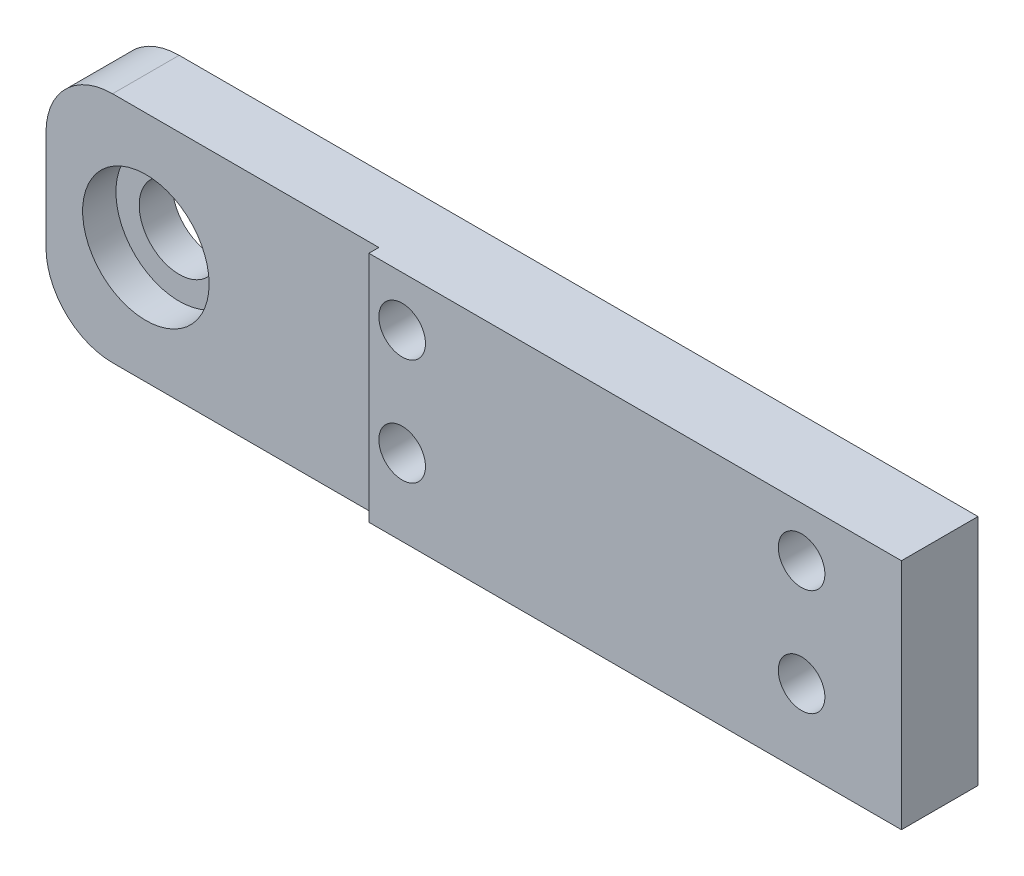
SolidWorks part; units mm, degrees
material "SKD11淬火HRC56-60"
ref_plane "前基準面" through (0, 0, 0) normal (0, 0, 1) x (1, 0, 0)
ref_plane "上基準面" through (0, 0, 0) normal (0, 1, 0) x (1, 0, 0)
ref_plane "右基準面" through (0, 0, 0) normal (1, 0, 0) x (0, 0, -1)
sketch "草图1" plane through (0, 0, 0) normal (0, 0, 1) x (1, 0, 0)
  line L1 (0, 0) -> (130, 0)
  line L2 (0, 0) -> (0, 35)
  line L3 (0, 35) -> (130, 35)
  line L4 (130, 0) -> (130, 35)
  dimension "D1" = 130
  dimension "D2" = 35
extrude "凸台-拉伸1" add sketch "草图1" along normal blind 10
sketch "草图2" plane through (0, 0, 10) normal (0, 0, 1) x (1, 0, 0)
  line L0 (0, 17.5) -> (130, 17.5) construction
  line L1 (0, 35) -> (0, 0) construction
  line L2 (130, 0) -> (130, 35) construction
  circle A0 centre (15, 17.5) radius 9.5
  dimension "D1" = 19
  dimension "D2" = 15
extrude "切除-拉伸1" cut sketch "草图2" against normal blind 5
sketch "草图3" plane through (0, 0, 5) normal (0, 0, 1) x (1, 0, 0)
  circle A0 centre (15, 17.5) radius 6
  dimension "D1" = 12
extrude "切除-拉伸2" cut sketch "草图3" against normal through all
fillet "圆角1" radius 10 2 edges at (0, 35, 5) (0, 0, 5)
sketch "草图4" plane through (0, 0, 10) normal (0, 0, 1) x (1, 0, 0)
  line L0 (130, 35) -> (10, 35) construction
  line L1 (130, 0) -> (50, 0)
  line L2 (130, 0) -> (130, 35)
  line L3 (130, 35) -> (50, 35)
  line L4 (50, 0) -> (50, 35)
  dimension "D1" = 80
extrude "凸台-拉伸2" add sketch "草图4" along normal blind 1.5
hole_wizard "M6 六角凹头螺钉的柱形沉头孔1" positions "草图6" profile "草图5" counterbore size "M6" standard "ISO" end condition through all
sketch "草图6" plane through (0, 0, 0) normal (0, 0, -1) x (-1, 0, 0)
  point P1 (-115, 11.5)
  point P4 (-115, 27.5)
  point P7 (-55, 27.5)
  point P10 (-55, 11.5)
sketch "草图5" plane through (115, 11.5, 0) normal (1, 0, 0) x (0, 1, 0)
  line L0 (0, 0) -> (0, 11.5)
  line L1 (0, 11.5) -> (3.5, 11.5)
  line L3 (3.5, 11.5) -> (3.5, 6)
  line L4 (3.5, 6) -> (5.5, 6)
  line L5 (5.5, 6) -> (5.5, 0)
  line L7 (5.5, 0) -> (0, 0)
  line L11 (0, -6.35) -> (0, 107.95) construction
  dimension "通孔孔直径" = 7
  dimension "通孔孔深度" = 11.5
  dimension "柱形沉头孔直径" = 11
  dimension "柱形沉头孔深度" = 6
